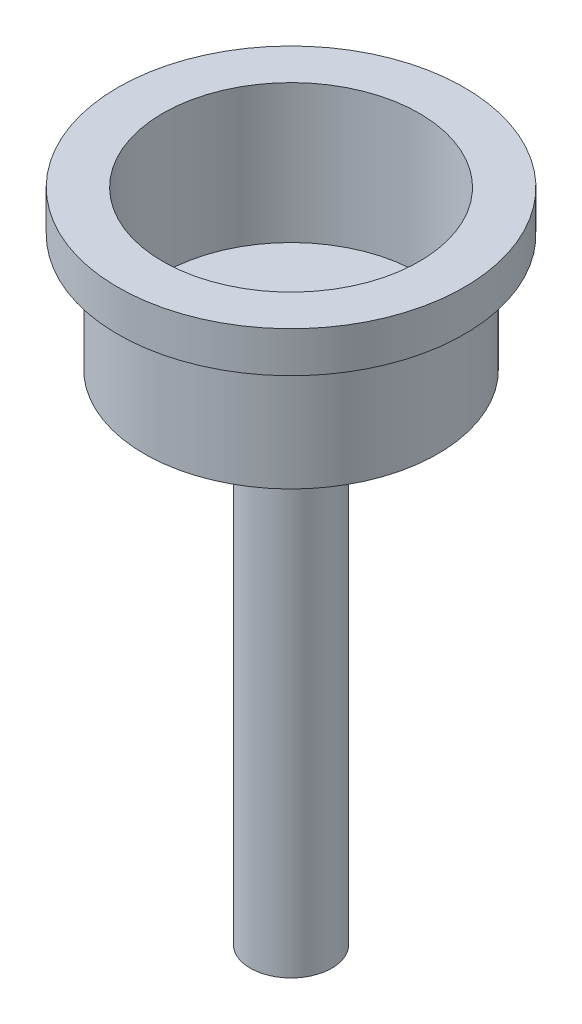
SolidWorks part; units mm, degrees
ref_plane "前视基准面" through (0, 0, 0) normal (0, 0, 1) x (1, 0, 0)
ref_plane "上视基准面" through (0, 0, 0) normal (0, 1, 0) x (1, 0, 0)
ref_plane "右视基准面" through (0, 0, 0) normal (1, 0, 0) x (0, 0, -1)
sketch "草图1" plane through (0, 0, 0) normal (0, 0, 1) x (1, 0, 0)
  line L0 (0, 0) -> (0.26, 0) construction
  line L1 (0.26, 0) -> (0.3, 0)
  line L2 (0.3, 0) -> (0.3, 3.67)
  line L3 (0.3, 3.67) -> (1.08, 3.67)
  line L4 (1.08, 3.67) -> (1.08, 4.53)
  line L5 (1.08, 4.53) -> (1.275, 4.53)
  line L6 (1.275, 4.53) -> (1.275, 4.83)
  line L7 (1.275, 4.83) -> (0, 4.83) construction
  line L8 (0, 4.83) -> (0, 0) construction
  line L9 (1.275, 4.83) -> (0.945, 4.83)
  line L10 (0.945, 4.83) -> (0.945, 3.81)
  line L11 (0.945, 3.81) -> (0.26, 3.81)
  line L12 (0.26, 3.81) -> (0.26, 0)
  dimension "D1" = 0.26
  dimension "D2" = 0.3
  dimension "D3" = 4.83
  dimension "D4" = 0.3
  dimension "D5" = 1.275
  dimension "D6" = 1.08
  dimension "D7" = 1.16
  dimension "D8" = 0.33
  dimension "D9" = 0.14
revolve "旋转1" add sketch "草图1" angle 360 about L8
